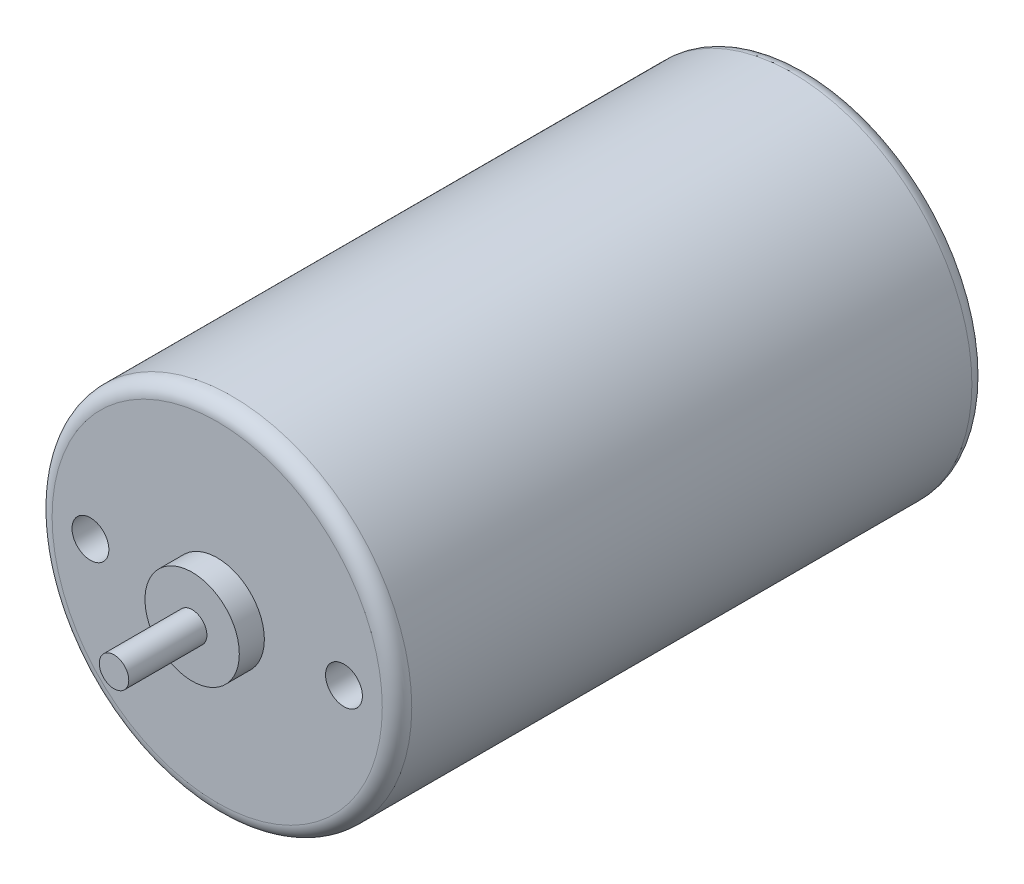
SolidWorks part; units mm, degrees
ref_plane "Plano frontal" through (0, 0, 0) normal (0, 0, 1) x (1, 0, 0)
ref_plane "Plano superior" through (0, 0, 0) normal (0, 1, 0) x (1, 0, 0)
ref_plane "Plano direito" through (0, 0, 0) normal (1, 0, 0) x (0, 0, -1)
sketch "Esboço1" plane through (0, 0, 0) normal (0, 0, 1) x (1, 0, 0)
  circle A0 centre (0, 0) radius 12.2
  dimension "D1" = 24.4
extrude "Ressalto-extrusão1" add sketch "Esboço1" along normal blind 40 contours A0
sketch "Esboço2" plane through (0, 0, 40) normal (0, 0, 1) x (1, 0, 0)
  circle A0 centre (0, 0) radius 3.2
  circle A1 centre (0, 0) radius 8.6 construction
  point P4 (-8.6, 0)
  point P5 (8.6, 0)
  dimension "D1" = 6.4
  dimension "D2" = 17.2
extrude "Ressalto-extrusão2" add sketch "Esboço2" along normal blind 1.7 contours A0
sketch "Esboço3" plane through (0, 0, 41.7) normal (0, 0, 1) x (1, 0, 0)
  circle A0 centre (0, 0) radius 1
  dimension "D1" = 2
extrude "Ressalto-extrusão3" add sketch "Esboço3" along normal blind 5.3
hole_wizard "Broca de rosquear para tarraxa de M31" positions "3DSketch1" profile "Esboço4" hole size "M3" standard "ISO"
sketch3d "3DSketch1"
  point P0 (-8.6, 0, 40)
  point P3 (8.6, 0, 40)
sketch "Esboço4" plane through (-8.6, 0, 40) normal (1, 0, 0) x (0, -1, 0)
  line L0 (0, 0) -> (0, 4.7511)
  line L1 (0, 4.7511) -> (1.25, 4)
  line L2 (1.25, 4) -> (1.25, 0)
  line L5 (1.25, 0) -> (0, 0)
  line L10 (0, 4.7511) -> (-1.25, 4) construction
  line L11 (0, -6.35) -> (0, 107.95) construction
  dimension "Hole Dia." = 2.5
  dimension "Hole Depth" = 4
  dimension "Drill Angle" = 118
fillet "Filete1" radius 1 1 edges at (12.2, 0, 40)
fillet "Filete2" radius 1 1 edges at (12.2, 0, 0)
